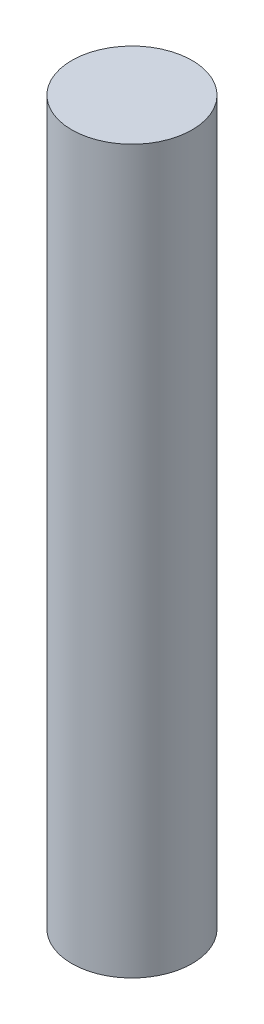
SolidWorks part; units mm, degrees
ref_plane "Front Plane" through (0, 0, 0) normal (0, 0, 1) x (1, 0, 0)
ref_plane "Top Plane" through (0, 0, 0) normal (0, 1, 0) x (1, 0, 0)
ref_plane "Right Plane" through (0, 0, 0) normal (1, 0, 0) x (0, 0, -1)
sketch "Sketch1" plane through (0, 0, 0) normal (0, 1, 0) x (1, 0, 0)
  circle A0 centre (0, 0) radius 2.1167
  dimension "D1" = 4.2333
extrude "Boss-Extrude1" add sketch "Sketch1" along normal blind 25.4
sketch "Sketch2" plane through (0, 25.4, 0) normal (0, 1, 0) x (1, 0, 0)
  point P0 (0, 0)
